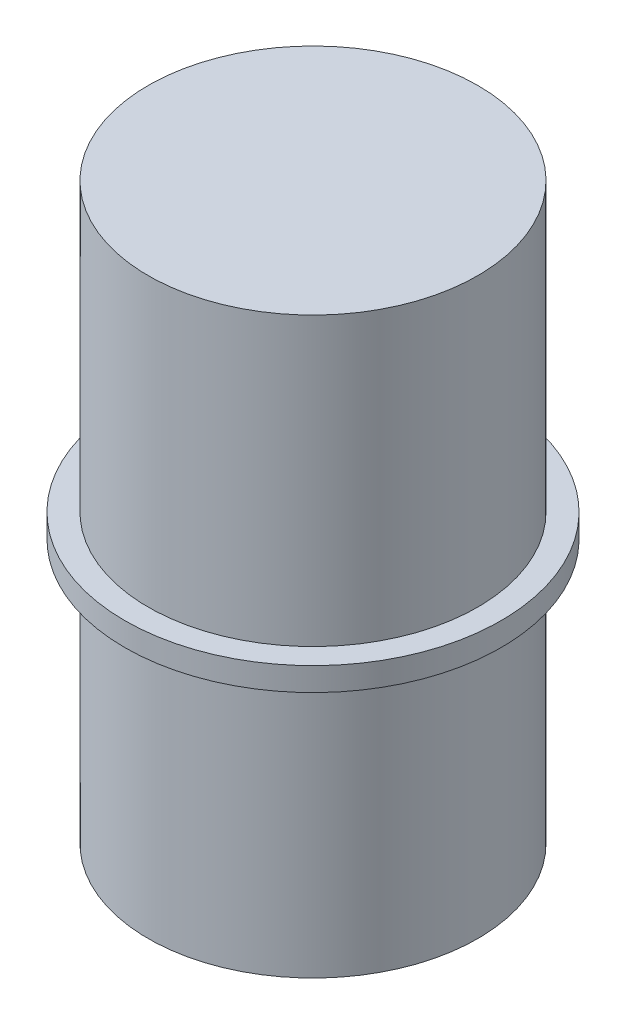
SolidWorks part; units mm, degrees
ref_plane "Front Plane" through (0, 0, 0) normal (0, 0, 1) x (1, 0, 0)
ref_plane "Top Plane" through (0, 0, 0) normal (0, 1, 0) x (1, 0, 0)
ref_plane "Right Plane" through (0, 0, 0) normal (1, 0, 0) x (0, 0, -1)
sketch "Sketch1" plane through (0, 0, 0) normal (0, 1, 0) x (1, 0, 0)
  circle A0 centre (0, 0) radius 10.9347
  dimension "D1" = 21.8694
extrude "Boss-Extrude1" add sketch "Sketch1" along normal blind 38.1
sketch "Sketch2" plane through (0, 38.1, 0) normal (0, 1, 0) x (1, 0, 0)
  line L0 (-10.9347, 0) -> (10.9347, 0)
  circle A0 centre (0, 0) radius 10.9347 construction
sketch "Sketch3" plane through (0, 0, 0) normal (0, -1, 0) x (1, 0, 0)
  line L0 (-10.9347, 0) -> (10.9347, 0)
sketch "Sketch5" plane through (0, 0, 0) normal (0, 0, 1) x (1, 0, 0)
  line L0 (-10.9347, 0) -> (-10.9347, 17.5) construction
  line L1 (-10.9347, 38.1) -> (-10.9347, 0) construction
  line L2 (-10.9347, 17.5) -> (-10.9347, 19.05)
  line L3 (-10.9347, 17.5) -> (-12.4847, 17.5)
  line L4 (-10.9347, 19.05) -> (-12.4847, 19.05)
  line L5 (-12.4847, 17.5) -> (-12.4847, 19.05)
  line L6 (0, 38.1) -> (0, 0) construction
  line L7 (-10.9347, 38.1) -> (10.9347, 38.1) construction
  dimension "D1" = 17.5
revolve "Revolve1" add sketch "Sketch5" angle 360 about L6
